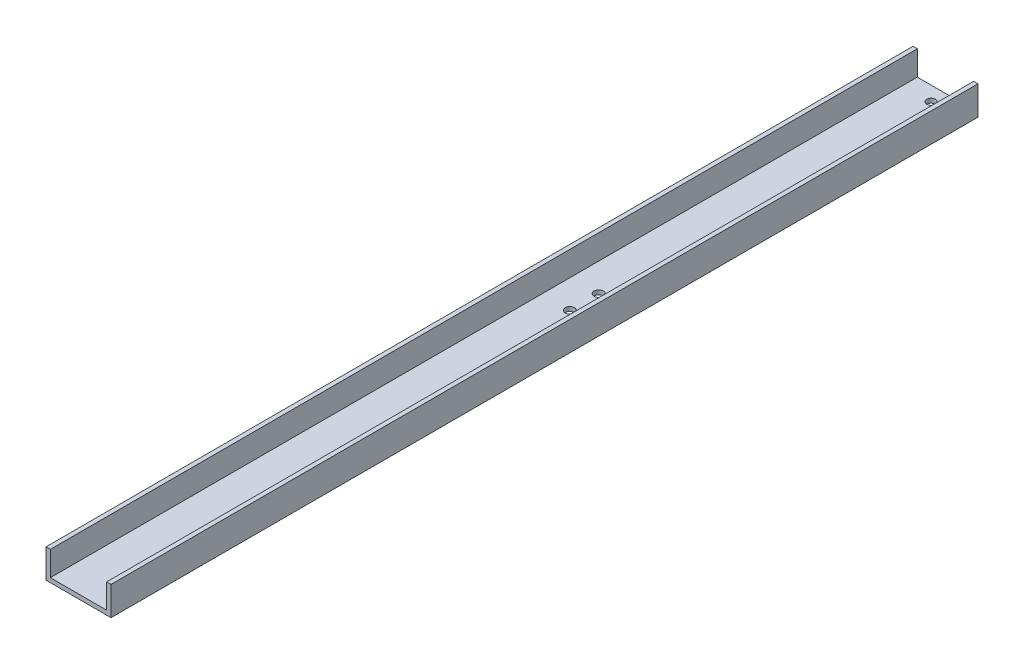
SolidWorks part; units mm, degrees
material "1060-H18 Barre (SS)"
ref_plane "Plan de face" through (0, 0, 0) normal (0, 0, 1) x (1, 0, 0)
ref_plane "Plan de dessus" through (0, 0, 0) normal (0, 1, 0) x (1, 0, 0)
ref_plane "Plan de droite" through (0, 0, 0) normal (1, 0, 0) x (0, 0, -1)
sketch "Esquisse1" plane through (0, 0, 0) normal (0, 0, 1) x (1, 0, 0)
  line L0 (-11.25, 0) -> (11.25, 0)
  line L1 (11.25, 0) -> (11.25, 10)
  line L2 (11.25, 10) -> (9.75, 10)
  line L3 (9.75, 10) -> (9.75, 1.5)
  line L4 (9.75, 1.5) -> (-9.75, 1.5)
  line L5 (-9.75, 1.5) -> (-9.75, 10)
  line L6 (-9.75, 10) -> (-11.25, 10)
  line L7 (-11.25, 10) -> (-11.25, 0)
  line L8 (0, 0) -> (0, 15.264) construction
  dimension "D1" = 1.5
  dimension "D2" = 1.5
  dimension "D3" = 10
  dimension "D4" = 22.5
extrude "Boss.-Extru.1" add sketch "Esquisse1" along normal blind 300
sketch "Esquisse2" plane through (0, 0, 0) normal (0, -1, 0) x (1, 0, 0)
  line L0 (0, 0) -> (0, 26.1584) construction
  line L1 (-11.25, 0) -> (11.25, 0) construction
  circle A0 centre (0, 120) radius 1.6
  circle A1 centre (0, 130) radius 1.6
  dimension "D1" = 3.2
  dimension "D2" = 3.2
  dimension "D3" = 10
  dimension "D4" = 120
extrude "Enlèv. mat.-Extru.1" cut sketch "Esquisse2" against normal through all
pattern_linear "Répétition linéaire1" [suppressed] count 2 spacing 115
hole_wizard "Ø3.0 (3) Durchmesser Langloch1" positions "Skizze2" profile "Skizze3" size "Ø3.0" standard "DIN" slot yes
sketch "Skizze2" plane through (0, 0, 0) normal (0, -1, 0) x (-1, 0, 0)
  line L0 (11.25, 0) -> (-11.25, 0) construction
  line L1 (11.25, -300) -> (11.25, 0) construction
  line L2 (-11.25, -300) -> (-11.25, 0) construction
  point P0 (0, -5)
  dimension "D1" = 5
  dimension "D2" = 11.25
  dimension "D3" = 11.25
sketch "Skizze3" plane through (0, 0, 5) normal (1, 0, 0) x (0, 0, -1)
  line L0 (0, 0) -> (0, 13.4013)
  line L1 (0, 13.4013) -> (1.5, 12.5)
  line L2 (1.5, 12.5) -> (1.5, 0)
  line L5 (1.5, 0) -> (0, 0)
  line L10 (0, 13.4013) -> (-1.5, 12.5) construction
  line L11 (0, -6.35) -> (0, 107.95) construction
  dimension "Bohrerdurchmesser" = 3
  dimension "Bohrungstiefe" = 12.5
  dimension "Spitzenwinkel" = 118
